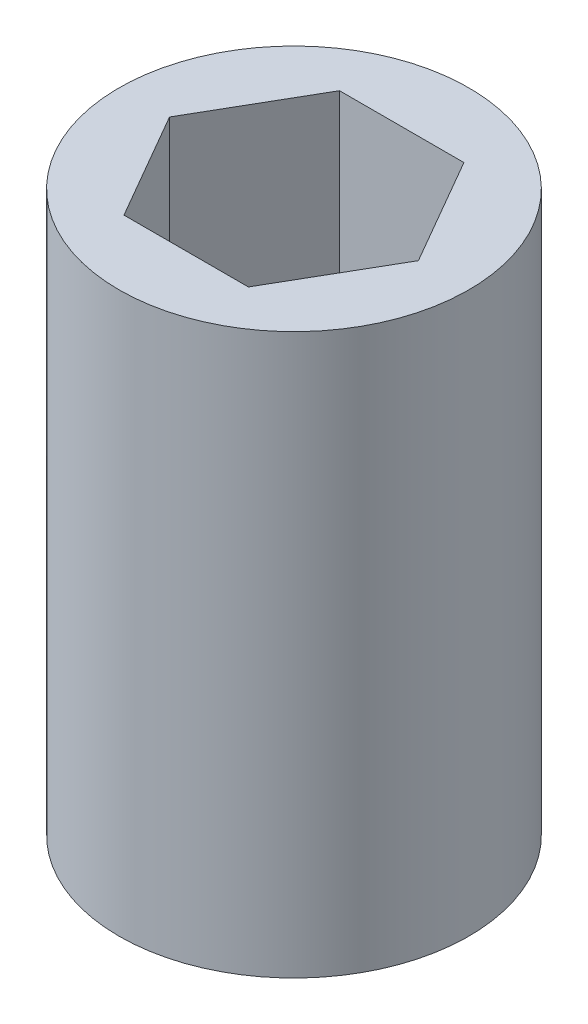
SolidWorks part; units mm, degrees
ref_plane "Front Plane" through (0, 0, 0) normal (0, 0, 1) x (1, 0, 0)
ref_plane "Top Plane" through (0, 0, 0) normal (0, 1, 0) x (1, 0, 0)
ref_plane "Right Plane" through (0, 0, 0) normal (1, 0, 0) x (0, 0, -1)
sketch "Sketch1" plane through (0, 0, 0) normal (0, 1, 0) x (1, 0, 0)
  line L1 (5.6459, 0) -> (2.823, 4.8895)
  line L2 (2.823, 4.8895) -> (-2.823, 4.8895)
  line L3 (-2.823, 4.8895) -> (-5.6459, 0)
  line L4 (-5.6459, 0) -> (-2.823, -4.8895)
  line L5 (-2.823, -4.8895) -> (2.823, -4.8895)
  line L6 (2.823, -4.8895) -> (5.6459, 0)
  circle A0 centre (0, 0) radius 4.8895 construction
  circle A1 centre (0, 0) radius 7.9375
  dimension "D1" = 9.779
  dimension "D2" = 15.875
extrude "Boss-Extrude1" add sketch "Sketch1" along normal blind 25.4
